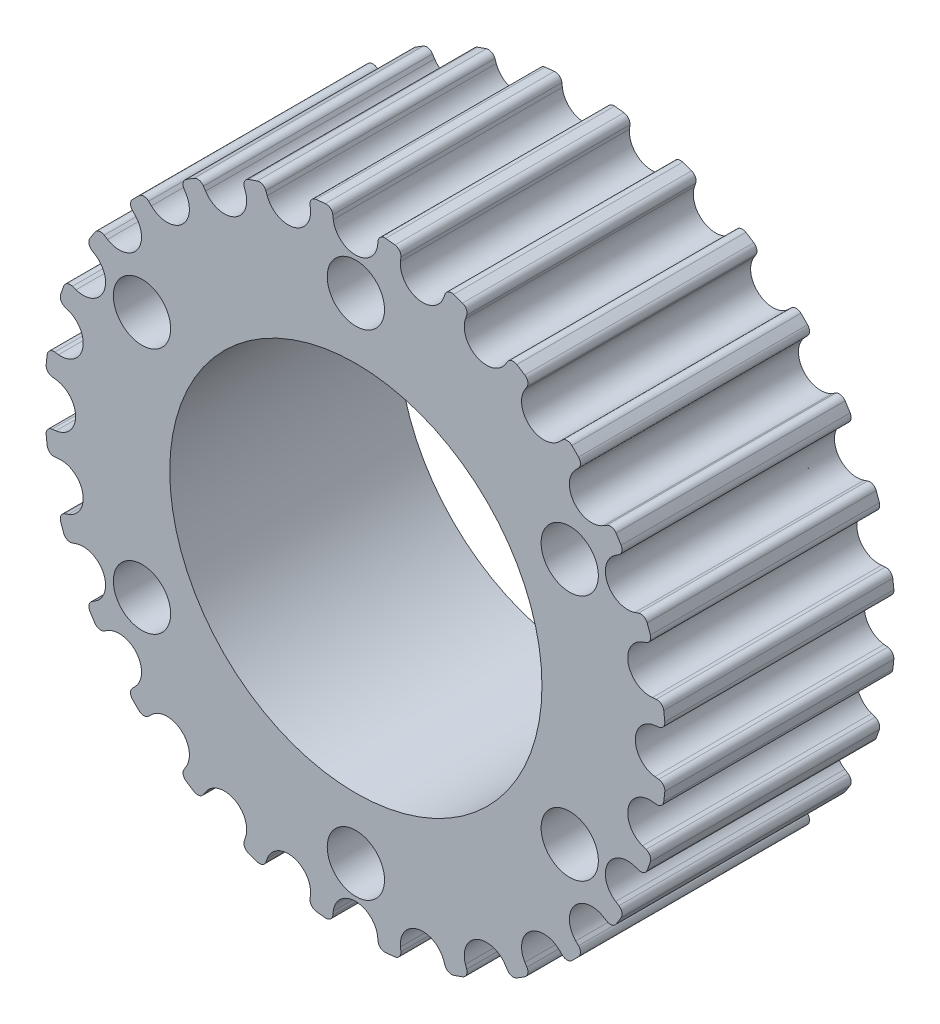
SolidWorks part; units mm, degrees
ref_plane "前视基准面" through (0, 0, 0) normal (0, 0, 1) x (1, 0, 0)
ref_plane "上视基准面" through (0, 0, 0) normal (0, 1, 0) x (1, 0, 0)
ref_plane "右视基准面" through (0, 0, 0) normal (1, 0, 0) x (0, 0, -1)
sketch "草图1" plane through (0, 0, 0) normal (0, 0, 1) x (1, 0, 0)
  line L36 (1.554, 21.1844) -> (1.521, 20.9158)
  line L37 (-1.5757, 20.9158) -> (-1.6087, 21.1844)
  line L38 (-3.2001, 21.0051) -> (-3.1724, 20.7359)
  line L39 (-6.1915, 20.0468) -> (-6.2835, 20.3013)
  line L40 (-7.7951, 19.7724) -> (-7.7082, 19.5161)
  line L41 (-10.4983, 18.1724) -> (-10.6446, 18.4002)
  line L42 (-12.0006, 17.5481) -> (-11.8588, 17.3175)
  line L43 (-14.28, 15.3868) -> (-14.4733, 15.5762)
  line L44 (-15.6057, 14.4438) -> (-15.4162, 14.2505)
  line L45 (-17.347, 11.8294) -> (-17.5776, 11.9711)
  line L46 (-18.4296, 10.6151) -> (-18.2019, 10.4689)
  line L47 (-19.5455, 7.6788) -> (-19.8018, 7.7656)
  line L48 (-20.3308, 6.254) -> (-20.0762, 6.1621)
  line L49 (-20.7653, 3.143) -> (-21.0345, 3.1706)
  line L50 (-21.2138, 1.5792) -> (-20.9452, 1.5463)
  line L51 (-20.9452, -1.5505) -> (-21.2138, -1.5835)
  line L52 (-21.0345, -3.1748) -> (-20.7653, -3.1472)
  line L53 (-20.0762, -6.1663) -> (-20.3308, -6.2583)
  line L54 (-19.8018, -7.7698) -> (-19.5455, -7.683)
  line L55 (-18.2019, -10.4731) -> (-18.4296, -10.6194)
  line L56 (-17.5776, -11.9753) -> (-17.347, -11.8336)
  line L57 (-15.4162, -14.2548) -> (-15.6057, -14.448)
  line L58 (-14.4733, -15.5804) -> (-14.28, -15.391)
  line L59 (-11.8588, -17.3218) -> (-12.0006, -17.5524)
  line L60 (-10.6446, -18.4044) -> (-10.4983, -18.1767)
  line L61 (-7.7082, -19.5203) -> (-7.7951, -19.7766)
  line L62 (-6.2835, -20.3056) -> (-6.1915, -20.051)
  line L63 (-3.1724, -20.7401) -> (-3.2001, -21.0093)
  line L64 (-1.6087, -21.1886) -> (-1.5757, -20.92)
  line L65 (1.521, -20.92) -> (1.554, -21.1886)
  line L66 (3.1454, -21.0093) -> (3.1178, -20.7401)
  line L67 (6.1369, -20.051) -> (6.2288, -20.3056)
  line L68 (7.7404, -19.7766) -> (7.6536, -19.5203)
  line L69 (10.4436, -18.1767) -> (10.5899, -18.4044)
  line L70 (11.9459, -17.5524) -> (11.8042, -17.3218)
  line L71 (14.2253, -15.391) -> (14.4186, -15.5804)
  line L72 (15.551, -14.448) -> (15.3615, -14.2548)
  line L73 (17.2923, -11.8336) -> (17.5229, -11.9753)
  line L74 (18.375, -10.6194) -> (18.1472, -10.4731)
  line L75 (19.4909, -7.683) -> (19.7472, -7.7698)
  line L76 (20.2761, -6.2583) -> (20.0216, -6.1663)
  line L77 (20.7107, -3.1472) -> (20.9799, -3.1748)
  line L78 (21.1592, -1.5835) -> (20.8906, -1.5505)
  line L79 (20.8906, 1.5463) -> (21.1592, 1.5792)
  line L80 (20.9799, 3.1706) -> (20.7107, 3.143)
  line L81 (20.0216, 6.1621) -> (20.2761, 6.254)
  line L82 (19.7472, 7.7656) -> (19.4909, 7.6788)
  line L83 (18.1472, 10.4689) -> (18.375, 10.6151)
  line L84 (17.5229, 11.9711) -> (17.2923, 11.8294)
  line L85 (15.3615, 14.2505) -> (15.551, 14.4438)
  line L86 (14.4186, 15.5762) -> (14.2253, 15.3868)
  line L87 (11.8042, 17.3175) -> (11.9459, 17.5481)
  line L88 (10.5899, 18.4002) -> (10.4436, 18.1724)
  line L89 (7.6536, 19.5161) -> (7.7404, 19.7724)
  line L90 (6.2288, 20.3013) -> (6.1369, 20.0468)
  line L91 (3.1178, 20.7359) -> (3.1454, 21.0051)
  circle A72 centre (0, 0) radius 12 construction
  arc A73 (3.1454, 21.0051) -> (2.7289, 21.5302) centre (2.6679, 21.0541) ccw
  arc A74 (2.7289, 21.5302) -> (2.077, 21.6037) centre (-0.0273, -0.0021) ccw
  arc A75 (2.077, 21.6037) -> (1.554, 21.1844) centre (2.0305, 21.1259) ccw
  arc A76 (-1.5757, 20.9158) -> (1.521, 20.9158) centre (-0.0273, 21.1059) ccw
  arc A77 (-1.6087, 21.1844) -> (-2.1316, 21.6037) centre (-2.0851, 21.1259) ccw
  arc A78 (-2.1316, 21.6037) -> (-2.7835, 21.5302) centre (-0.0273, -0.0021) ccw
  arc A79 (-2.7835, 21.5302) -> (-3.2001, 21.0051) centre (-2.7226, 21.0541) ccw
  arc A80 (-6.1915, 20.0468) -> (-3.1724, 20.7359) centre (-4.7243, 20.5767) ccw
  arc A81 (-6.2835, 20.3013) -> (-6.8866, 20.5937) centre (-6.7349, 20.1383) ccw
  arc A82 (-6.8866, 20.5937) -> (-7.5058, 20.377) centre (-0.0273, -0.0021) ccw
  arc A83 (-7.5058, 20.377) -> (-7.7951, 19.7724) centre (-7.3404, 19.9264) ccw
  arc A84 (-10.4983, 18.1724) -> (-7.7082, 19.5161) centre (-9.1857, 19.0155) ccw
  arc A85 (-10.6446, 18.4002) -> (-11.2976, 18.551) centre (-11.0484, 18.1407) ccw
  arc A86 (-11.2976, 18.551) -> (-11.8531, 18.202) centre (-0.0273, -0.0021) ccw
  arc A87 (-11.8531, 18.202) -> (-12.0006, 17.5481) centre (-11.5916, 17.7994) ccw
  arc A88 (-14.28, 15.3868) -> (-11.8588, 17.3175) centre (-13.1879, 16.5008) ccw
  arc A89 (-14.4733, 15.5762) -> (-15.1435, 15.5779) centre (-14.8093, 15.2334) ccw
  arc A90 (-15.1435, 15.5779) -> (-15.6074, 15.1141) centre (-0.0273, -0.0021) ccw
  arc A91 (-15.6074, 15.1141) -> (-15.6057, 14.4438) centre (-15.2629, 14.7798) ccw
  arc A92 (-17.347, 11.8294) -> (-15.4162, 14.2505) centre (-16.5302, 13.1585) ccw
  arc A93 (-17.5776, 11.9711) -> (-18.2314, 11.8236) centre (-17.8289, 11.5622) ccw
  arc A94 (-18.2314, 11.8236) -> (-18.5804, 11.2682) centre (-0.0273, -0.0021) ccw
  arc A95 (-18.5804, 11.2682) -> (-18.4296, 10.6151) centre (-18.1702, 11.019) ccw
  arc A96 (-19.5455, 7.6788) -> (-18.2019, 10.4689) centre (-19.045, 9.1563) ccw
  arc A97 (-19.8018, 7.7656) -> (-20.4065, 7.4764) centre (-19.9559, 7.311) ccw
  arc A98 (-20.4065, 7.4764) -> (-20.6231, 6.8572) centre (-0.0273, -0.0021) ccw
  arc A99 (-20.6231, 6.8572) -> (-20.3308, 6.254) centre (-20.1677, 6.7055) ccw
  arc A100 (-20.7653, 3.143) -> (-20.0762, 6.1621) centre (-20.6061, 4.6949) ccw
  arc A101 (-21.0345, 3.1706) -> (-21.5596, 2.7541) centre (-21.0835, 2.6931) ccw
  arc A102 (-21.5596, 2.7541) -> (-21.6331, 2.1022) centre (-0.0273, -0.0021) ccw
  arc A103 (-21.6331, 2.1022) -> (-21.2138, 1.5792) centre (-21.1554, 2.0557) ccw
  arc A104 (-20.9452, -1.5505) -> (-20.9452, 1.5463) centre (-21.1353, -0.0021) ccw
  arc A105 (-21.2138, -1.5835) -> (-21.6331, -2.1064) centre (-21.1554, -2.0599) ccw
  arc A106 (-21.6331, -2.1064) -> (-21.5596, -2.7583) centre (-0.0273, -0.0021) ccw
  arc A107 (-21.5596, -2.7583) -> (-21.0345, -3.1748) centre (-21.0835, -2.6974) ccw
  arc A108 (-20.0762, -6.1663) -> (-20.7653, -3.1472) centre (-20.6061, -4.6991) ccw
  arc A109 (-20.3308, -6.2583) -> (-20.6231, -6.8614) centre (-20.1677, -6.7097) ccw
  arc A110 (-20.6231, -6.8614) -> (-20.4065, -7.4806) centre (-0.0273, -0.0021) ccw
  arc A111 (-20.4065, -7.4806) -> (-19.8018, -7.7698) centre (-19.9559, -7.3152) ccw
  arc A112 (-18.2019, -10.4731) -> (-19.5455, -7.683) centre (-19.045, -9.1605) ccw
  arc A113 (-18.4296, -10.6194) -> (-18.5804, -11.2724) centre (-18.1702, -11.0232) ccw
  arc A114 (-18.5804, -11.2724) -> (-18.2314, -11.8279) centre (-0.0273, -0.0021) ccw
  arc A115 (-18.2314, -11.8279) -> (-17.5776, -11.9753) centre (-17.8289, -11.5664) ccw
  arc A116 (-15.4162, -14.2548) -> (-17.347, -11.8336) centre (-16.5302, -13.1627) ccw
  arc A117 (-15.6057, -14.448) -> (-15.6074, -15.1183) centre (-15.2629, -14.7841) ccw
  arc A118 (-15.6074, -15.1183) -> (-15.1435, -15.5822) centre (-0.0273, -0.0021) ccw
  arc A119 (-15.1435, -15.5822) -> (-14.4733, -15.5804) centre (-14.8093, -15.2377) ccw
  arc A120 (-11.8588, -17.3218) -> (-14.28, -15.391) centre (-13.1879, -16.505) ccw
  arc A121 (-12.0006, -17.5524) -> (-11.8531, -18.2062) centre (-11.5916, -17.8037) ccw
  arc A122 (-11.8531, -18.2062) -> (-11.2976, -18.5552) centre (-0.0273, -0.0021) ccw
  arc A123 (-11.2976, -18.5552) -> (-10.6446, -18.4044) centre (-11.0484, -18.145) ccw
  arc A124 (-7.7082, -19.5203) -> (-10.4983, -18.1767) centre (-9.1857, -19.0198) ccw
  arc A125 (-7.7951, -19.7766) -> (-7.5058, -20.3813) centre (-7.3404, -19.9306) ccw
  arc A126 (-7.5058, -20.3813) -> (-6.8866, -20.5979) centre (-0.0273, -0.0021) ccw
  arc A127 (-6.8866, -20.5979) -> (-6.2835, -20.3056) centre (-6.7349, -20.1425) ccw
  arc A128 (-3.1724, -20.7401) -> (-6.1915, -20.051) centre (-4.7243, -20.5809) ccw
  arc A129 (-3.2001, -21.0093) -> (-2.7835, -21.5344) centre (-2.7226, -21.0583) ccw
  arc A130 (-2.7835, -21.5344) -> (-2.1316, -21.6079) centre (-0.0273, -0.0021) ccw
  arc A131 (-2.1316, -21.6079) -> (-1.6087, -21.1886) centre (-2.0851, -21.1301) ccw
  arc A132 (1.521, -20.92) -> (-1.5757, -20.92) centre (-0.0273, -21.1101) ccw
  arc A133 (1.554, -21.1886) -> (2.077, -21.6079) centre (2.0305, -21.1301) ccw
  arc A134 (2.077, -21.6079) -> (2.7289, -21.5344) centre (-0.0273, -0.0021) ccw
  arc A135 (2.7289, -21.5344) -> (3.1454, -21.0093) centre (2.6679, -21.0583) ccw
  arc A136 (6.1369, -20.051) -> (3.1178, -20.7401) centre (4.6696, -20.5809) ccw
  arc A137 (6.2288, -20.3056) -> (6.832, -20.5979) centre (6.6803, -20.1425) ccw
  arc A138 (6.832, -20.5979) -> (7.4512, -20.3813) centre (-0.0273, -0.0021) ccw
  arc A139 (7.4512, -20.3813) -> (7.7404, -19.7766) centre (7.2858, -19.9306) ccw
  arc A140 (10.4436, -18.1767) -> (7.6536, -19.5203) centre (9.1311, -19.0198) ccw
  arc A141 (10.5899, -18.4044) -> (11.243, -18.5552) centre (10.9938, -18.145) ccw
  arc A142 (11.243, -18.5552) -> (11.7984, -18.2062) centre (-0.0273, -0.0021) ccw
  arc A143 (11.7984, -18.2062) -> (11.9459, -17.5524) centre (11.5369, -17.8037) ccw
  arc A144 (14.2253, -15.391) -> (11.8042, -17.3218) centre (13.1333, -16.505) ccw
  arc A145 (14.4186, -15.5804) -> (15.0889, -15.5822) centre (14.7546, -15.2377) ccw
  arc A146 (15.0889, -15.5822) -> (15.5527, -15.1183) centre (-0.0273, -0.0021) ccw
  arc A147 (15.5527, -15.1183) -> (15.551, -14.448) centre (15.2082, -14.7841) ccw
  arc A148 (17.2923, -11.8336) -> (15.3615, -14.2548) centre (16.4756, -13.1627) ccw
  arc A149 (17.5229, -11.9753) -> (18.1768, -11.8279) centre (17.7742, -11.5664) ccw
  arc A150 (18.1768, -11.8279) -> (18.5258, -11.2724) centre (-0.0273, -0.0021) ccw
  arc A151 (18.5258, -11.2724) -> (18.375, -10.6194) centre (18.1155, -11.0232) ccw
  arc A152 (19.4909, -7.683) -> (18.1472, -10.4731) centre (18.9903, -9.1605) ccw
  arc A153 (19.7472, -7.7698) -> (20.3518, -7.4806) centre (19.9012, -7.3152) ccw
  arc A154 (20.3518, -7.4806) -> (20.5685, -6.8614) centre (-0.0273, -0.0021) ccw
  arc A155 (20.5685, -6.8614) -> (20.2761, -6.2583) centre (20.1131, -6.7097) ccw
  arc A156 (20.7107, -3.1472) -> (20.0216, -6.1663) centre (20.5515, -4.6991) ccw
  arc A157 (20.9799, -3.1748) -> (21.505, -2.7583) centre (21.0289, -2.6974) ccw
  arc A158 (21.505, -2.7583) -> (21.5784, -2.1064) centre (-0.0273, -0.0021) ccw
  arc A159 (21.5784, -2.1064) -> (21.1592, -1.5835) centre (21.1007, -2.0599) ccw
  arc A160 (20.8906, 1.5463) -> (20.8906, -1.5505) centre (21.0807, -0.0021) ccw
  arc A161 (21.1592, 1.5792) -> (21.5784, 2.1022) centre (21.1007, 2.0557) ccw
  arc A162 (21.5784, 2.1022) -> (21.505, 2.7541) centre (-0.0273, -0.0021) ccw
  arc A163 (21.505, 2.7541) -> (20.9799, 3.1706) centre (21.0289, 2.6931) ccw
  arc A164 (20.0216, 6.1621) -> (20.7107, 3.143) centre (20.5515, 4.6949) ccw
  arc A165 (20.2761, 6.254) -> (20.5685, 6.8572) centre (20.1131, 6.7055) ccw
  arc A166 (20.5685, 6.8572) -> (20.3518, 7.4764) centre (-0.0273, -0.0021) ccw
  arc A167 (20.3518, 7.4764) -> (19.7472, 7.7656) centre (19.9012, 7.311) ccw
  arc A168 (18.1472, 10.4689) -> (19.4909, 7.6788) centre (18.9903, 9.1563) ccw
  arc A169 (18.375, 10.6151) -> (18.5258, 11.2682) centre (18.1155, 11.019) ccw
  arc A170 (18.5258, 11.2682) -> (18.1768, 11.8236) centre (-0.0273, -0.0021) ccw
  arc A171 (18.1768, 11.8236) -> (17.5229, 11.9711) centre (17.7742, 11.5622) ccw
  arc A172 (15.3615, 14.2505) -> (17.2923, 11.8294) centre (16.4756, 13.1585) ccw
  arc A173 (15.551, 14.4438) -> (15.5527, 15.1141) centre (15.2082, 14.7798) ccw
  arc A174 (15.5527, 15.1141) -> (15.0889, 15.5779) centre (-0.0273, -0.0021) ccw
  arc A175 (15.0889, 15.5779) -> (14.4186, 15.5762) centre (14.7546, 15.2334) ccw
  arc A176 (11.8042, 17.3175) -> (14.2253, 15.3868) centre (13.1333, 16.5008) ccw
  arc A177 (11.9459, 17.5481) -> (11.7984, 18.202) centre (11.5369, 17.7994) ccw
  arc A178 (11.7984, 18.202) -> (11.243, 18.551) centre (-0.0273, -0.0021) ccw
  arc A179 (11.243, 18.551) -> (10.5899, 18.4002) centre (10.9938, 18.1407) ccw
  arc A180 (7.6536, 19.5161) -> (10.4436, 18.1724) centre (9.1311, 19.0155) ccw
  arc A181 (7.7404, 19.7724) -> (7.4512, 20.377) centre (7.2858, 19.9264) ccw
  arc A182 (7.4512, 20.377) -> (6.832, 20.5937) centre (-0.0273, -0.0021) ccw
  arc A183 (6.832, 20.5937) -> (6.2288, 20.3013) centre (6.6803, 20.1383) ccw
  arc A184 (3.1178, 20.7359) -> (6.1369, 20.0468) centre (4.6696, 20.5767) ccw
  circle A185 centre (-0.0273, -0.0021) radius 7.5
  dimension "D1" = 15
  dimension "D2" = 24
extrude "凸台-拉伸1" add sketch "草图1" along normal blind 16
sketch "草图7" plane through (0, 0, 0) normal (0, 0, -1) x (-1, 0, 0)
  circle A0 centre (0, 0) radius 17.25 construction
  circle A1 centre (0, 17.25) radius 2
  circle A2 centre (14.9389, 8.625) radius 2
  circle A3 centre (14.9389, -8.625) radius 2
  circle A4 centre (0, -17.25) radius 2
  circle A5 centre (-14.9389, -8.625) radius 2
  circle A6 centre (-14.9389, 8.625) radius 2
  circle A7 centre (0, 0) radius 13
  point P3 (0, 17.25)
  point P6 (14.9389, 8.625)
  point P7 (14.9389, -8.625)
  point P8 (0, -17.25)
  point P9 (-14.9389, -8.625)
  point P10 (-14.9389, 8.625)
  point P11 (0, 0)
  point P24 (0, 0)
  dimension "D1" = 34.5
  dimension "D3" = 4
  dimension "D5" = 26
  dimension "D2" = 6
  dimension "D4" = 6
extrude "切除-拉伸1" cut sketch "草图7" against normal blind 41
